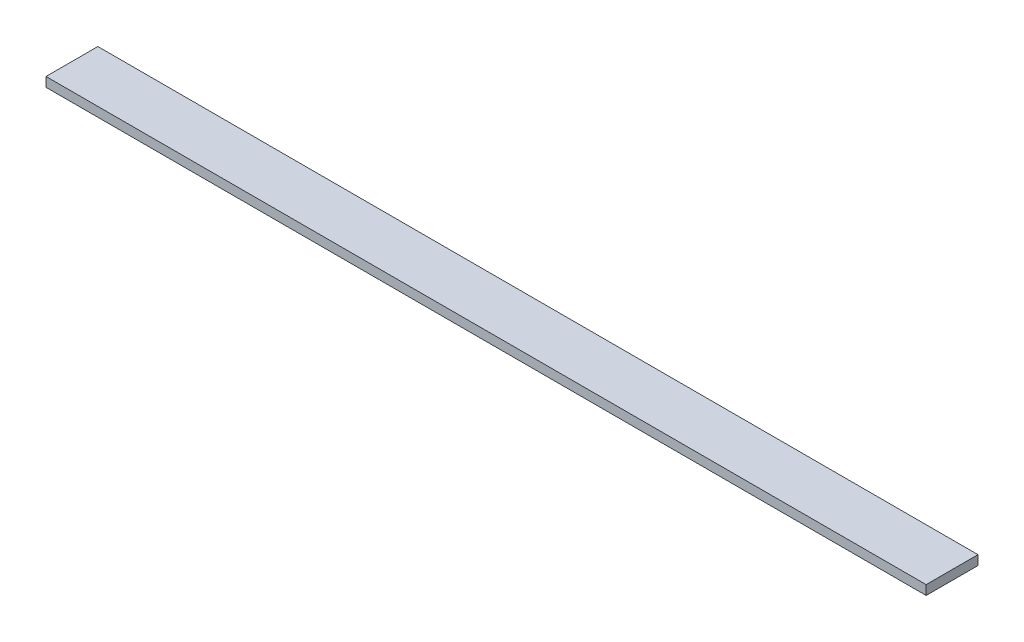
SolidWorks part; units mm, degrees
ref_plane "Front Plane" through (0, 0, 0) normal (0, 0, 1) x (1, 0, 0)
ref_plane "Top Plane" through (0, 0, 0) normal (0, 1, 0) x (1, 0, 0)
ref_plane "Right Plane" through (0, 0, 0) normal (1, 0, 0) x (0, 0, -1)
sketch "Sketch1" plane through (0, 0, 0) normal (0, 1, 0) x (1, 0, 0)
  line L1 (-46.675, -2.75) -> (46.675, -2.75)
  line L2 (-46.675, -2.75) -> (-46.675, 2.75)
  line L3 (-46.675, 2.75) -> (46.675, 2.75)
  line L4 (46.675, -2.75) -> (46.675, 2.75)
  line L5 (-46.675, -2.75) -> (46.675, 2.75) construction
  line L6 (-46.675, 2.75) -> (46.675, -2.75) construction
  point P0 (0, 0)
  dimension "D1" = 93.35
  dimension "D2" = 5.5
extrude "Boss-Extrude1" add sketch "Sketch1" along normal blind 1
